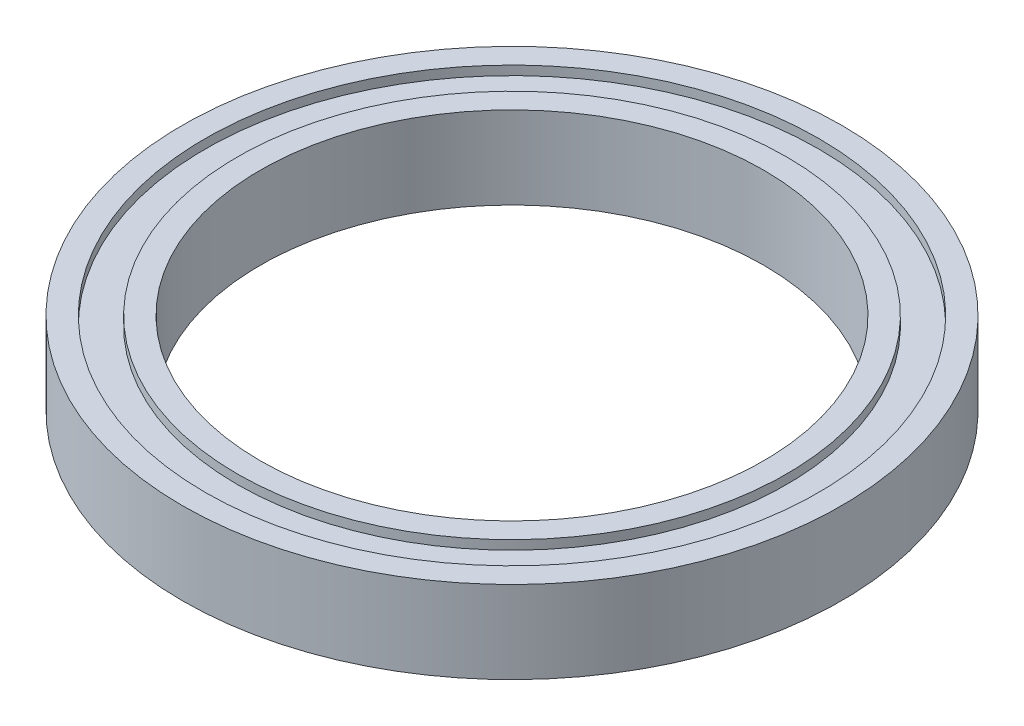
SolidWorks part; units mm, degrees
ref_plane "Front Plane" through (0, 0, 0) normal (0, 0, 1) x (1, 0, 0)
ref_plane "Top Plane" through (0, 0, 0) normal (0, 1, 0) x (1, 0, 0)
ref_plane "Right Plane" through (0, 0, 0) normal (1, 0, 0) x (0, 0, -1)
sketch "Sketch1" plane through (0, 0, 0) normal (0, 1, 0) x (1, 0, 0)
  circle A0 centre (0, 0) radius 27.5
  circle A1 centre (0, 0) radius 36
  dimension "D1" = 55
  dimension "D2" = 72
extrude "Boss-Extrude1" add sketch "Sketch1" along normal blind 9
sketch "Sketch2" plane through (0, 9, 0) normal (0, 1, 0) x (1, 0, 0)
  circle A2 centre (0, 0) radius 36 construction
  circle A3 centre (0, 0) radius 36
  circle A4 centre (0, 0) radius 33.5
  circle A5 centre (0, 0) radius 30
  dimension "D1" = 67
  dimension "D2" = 60
extrude "Cut-Extrude1" cut sketch "Sketch2" against normal blind 1 contours A4 A5
ref_plane "Plane1" through (0, 4.5, 0) normal (0, 1, 0) x (1, 0, 0)
mirror "Mirror1" about plane through (0, 4.5, 0) normal (0, 1, 0) of "Cut-Extrude1"
